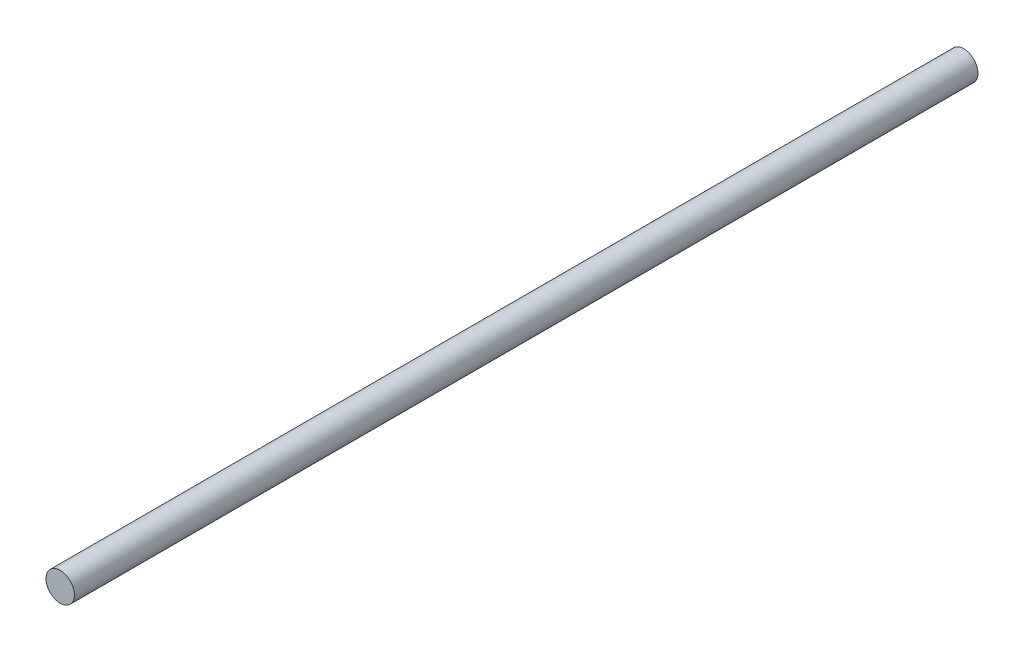
SolidWorks part; units mm, degrees
ref_plane "Front Plane" through (0, 0, 0) normal (0, 0, 1) x (1, 0, 0)
ref_plane "Top Plane" through (0, 0, 0) normal (0, 1, 0) x (1, 0, 0)
ref_plane "Right Plane" through (0, 0, 0) normal (1, 0, 0) x (0, 0, -1)
sketch "Sketch1" plane through (0, 0, 0) normal (0, 0, 1) x (1, 0, 0)
  circle A0 centre (0, 0) radius 3.175
  dimension "D1" = 6.35
extrude "Boss-Extrude1" add sketch "Sketch1" against normal blind 201.422
